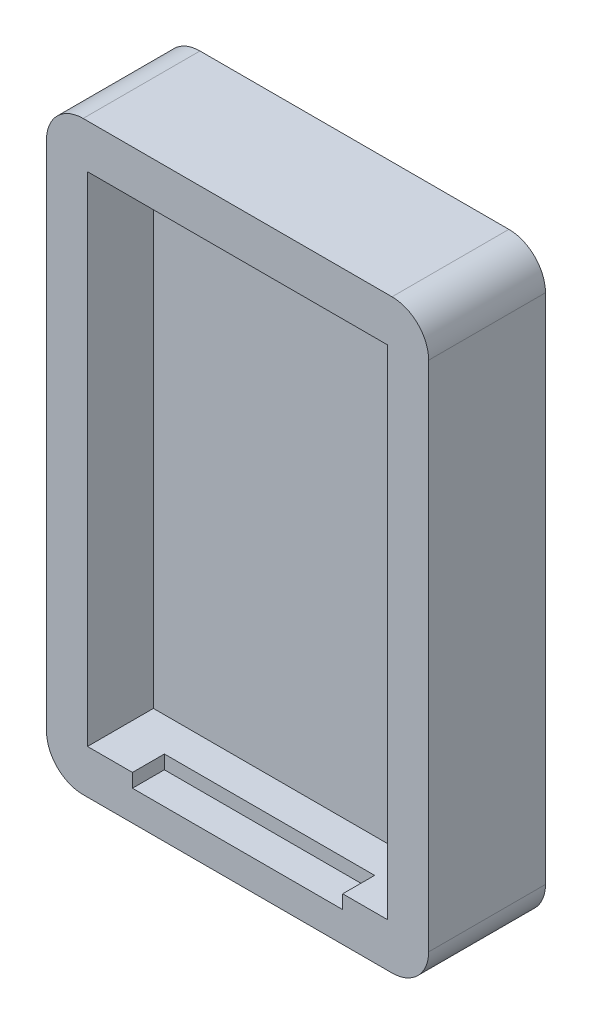
SolidWorks part; units mm, degrees
ref_plane "Plan de face" through (0, 0, 0) normal (0, 0, 1) x (1, 0, 0)
ref_plane "Plan de dessus" through (0, 0, 0) normal (0, 1, 0) x (1, 0, 0)
ref_plane "Plan de droite" through (0, 0, 0) normal (1, 0, 0) x (0, 0, -1)
sketch "Esquisse4" plane through (0, 0, 0) normal (0, 0, 1) x (1, 0, 0)
  line L1 (-133.582, 213.2829) -> (-88.582, 213.2829)
  line L2 (-133.582, 213.2829) -> (-133.582, 144.3174)
  line L3 (-133.582, 144.3174) -> (-88.582, 144.3174)
  line L4 (-88.582, 213.2829) -> (-88.582, 144.3174)
extrude "Boss.-Extru.2" add sketch "Esquisse4" along normal blind 20
fillet "Congé6" radius 4.3103 4 edges at (-88.582, 144.3174, 10) (-133.582, 144.3174, 10) (-88.582, 213.2829, 10) (-133.582, 213.2829, 10)
sketch "Esquisse9" plane through (0, 0, 20) normal (0, 0, 1) x (1, 0, 0)
  line L0 (-88.582, 148.6277) -> (-88.582, 208.9726) construction
  line L7 (-128.7544, 208.1129) -> (-93.4096, 208.1129)
  line L8 (-128.7544, 208.1129) -> (-128.7544, 149.4922)
  line L9 (-128.7544, 149.4922) -> (-93.4096, 149.4922)
  line L10 (-93.4096, 208.1129) -> (-93.4096, 149.4922)
  line L12 (-92.8923, 213.2829) -> (-129.2716, 213.2829) construction
  line L14 (-129.2716, 144.3174) -> (-92.8923, 144.3174) construction
  line L15 (-133.582, 208.9726) -> (-133.582, 148.6277) construction
  dimension "D1" = 5.17
  dimension "D2" = 5.1748
  dimension "D3" = 4.8276
  dimension "D4" = 4.8276
extrude "Enlèv. mat.-Extru.7" cut sketch "Esquisse9" against normal blind 14
sketch "Esquisse10" plane through (0, 0, 20) normal (0, 0, 1) x (1, 0, 0)
  line L0 (-128.7544, 149.4922) -> (-93.4096, 149.4922) construction
  line L1 (-123.4613, 149.4922) -> (-98.7027, 149.4922)
  line L2 (-123.4613, 149.4922) -> (-123.4613, 147.8786)
  line L3 (-123.4613, 147.8786) -> (-98.7027, 147.8786)
  line L4 (-98.7027, 149.4922) -> (-98.7027, 147.8786)
  line L5 (-128.7544, 208.1129) -> (-128.7544, 149.4922) construction
  line L6 (-93.4096, 149.4922) -> (-93.4096, 208.1129) construction
  line L7 (-129.2716, 144.3174) -> (-92.8923, 144.3174) construction
  dimension "D1" = 5.2931
  dimension "D2" = 5.2931
  dimension "D3" = 3.5612
extrude "Enlèv. mat.-Extru.8" cut sketch "Esquisse10" against normal blind 10
sketch "Esquisse12" plane through (0, 0, 20) normal (0, 0, 1) x (1, 0, 0)
  line L0 (-133.582, 208.9726) -> (-133.582, 148.6277) construction
  line L1 (-133.582, 213.2829) -> (-88.582, 213.2829)
  line L2 (-133.582, 213.2829) -> (-133.582, 144.3174)
  line L3 (-133.582, 144.3174) -> (-88.582, 144.3174)
  line L4 (-88.582, 213.2829) -> (-88.582, 144.3174)
  line L5 (-88.582, 148.6277) -> (-88.582, 208.9726) construction
  line L6 (-92.8923, 213.2829) -> (-129.2716, 213.2829) construction
  line L7 (-129.2716, 144.3174) -> (-92.8923, 144.3174) construction
extrude "Enlèv. mat.-Extru.11" cut sketch "Esquisse12" against normal blind 6.24
sketch "Esquisse14" plane through (0, 0, 0) normal (0, 0, 1) x (1, 0, 0)
  line L13 (-125.0527, 168.9899) -> (-131.2628, 168.9899)
  line L14 (-125.0527, 162.4542) -> (-125.0527, 168.9899)
  line L15 (-131.2628, 162.4542) -> (-125.0527, 162.4542)
  line L16 (-131.2628, 168.9899) -> (-131.2628, 162.4542)
  line L17 (-125.1661, 194.7047) -> (-131.2628, 194.7047)
  line L18 (-124.9394, 175.3053) -> (-125.1661, 194.7047)
  line L19 (-131.2628, 175.3053) -> (-124.9394, 175.3053)
  line L20 (-131.2628, 194.7047) -> (-131.2628, 175.3053)
  ellipse E0 centre (-104.3965, 172.8437) end of major axis (-90.1201, 172.3882) minor radius 14.1069 (-90.1201, 172.3882) -> (-118.6728, 173.2991) cw
  ellipse E1 centre (-104.3965, 172.8437) end of major axis (-118.6728, 173.2991) minor radius 14.1069 (-118.6728, 173.2991) -> (-90.1201, 172.3882) ccw
  spline S3 degree 3 poles (-116.6146, 165.5464) (-102.2915, 166.2996) (-106.3978, 182.9008) (-97.3522, 189.5698) knots 0 0 0 0 1 1 1 1
  spline S4 degree 3 poles (-104.3193, 199.2004) (-98.9988, 190.7419) (-90.3392, 183.1381) (-90.1201, 172.3882) knots 0 0 0 0 1 1 1 1
  spline S5 degree 3 poles (-104.3193, 199.2004) (-109.6446, 191.272) (-117.4961, 183.3244) (-118.6728, 173.2991) knots 0 0 0 0 1 1 1 1
  point P1 (0, 0)
  point P7 (0, 0)
  point P8 (0, 0)
  point P9 (0, 0)
  point P10 (0, 0)
  point P11 (0, 0)
  point P12 (0, 0)
extrude "Enlèv. mat.-Extru.15" cut sketch "Esquisse14" along normal blind 3 contours S4 S5 E1 S3 | L17 L20 L19 L18 | L13 L16 L15 L14 | S4 S3 E0
scale "Echelle2" scale about centroid uniform scaling yes scale factor 1.16
